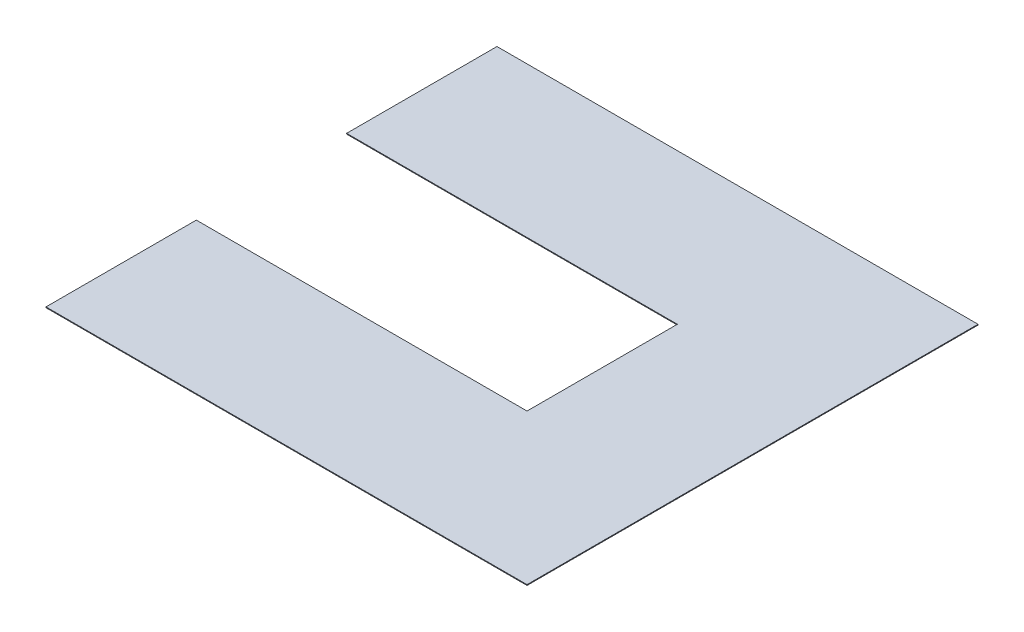
SolidWorks part; units mm, degrees
ref_plane "Front Plane" through (0, 0, 0) normal (0, 0, 1) x (1, 0, 0)
ref_plane "Top Plane" through (0, 0, 0) normal (0, 1, 0) x (1, 0, 0)
ref_plane "Right Plane" through (0, 0, 0) normal (1, 0, 0) x (0, 0, -1)
sketch "Sketch1" plane through (0, 0, 0) normal (0, 1, 0) x (1, 0, 0)
  line L10 (0, 0) -> (8, 0) construction
  line L11 (0, 3.75) -> (0, 1.25)
  line L12 (0, 1.25) -> (5.5, 1.25)
  line L13 (5.5, 1.25) -> (5.5, -1.25)
  line L14 (5.5, -1.25) -> (0, -1.25)
  line L15 (0, -1.25) -> (0, -3.75)
  line L16 (0, -3.75) -> (8, -3.75)
  line L17 (8, -3.75) -> (8, 3.75)
  line L18 (8, 3.75) -> (0, 3.75)
  dimension "D1" = 7.5
  dimension "D2" = 1.25
  dimension "D3" = 2.5
  dimension "D4" = 8
  dimension "D5" = 2.5
extrude "Boss-Extrude1" add sketch "Sketch1" along normal blind 0.0126
